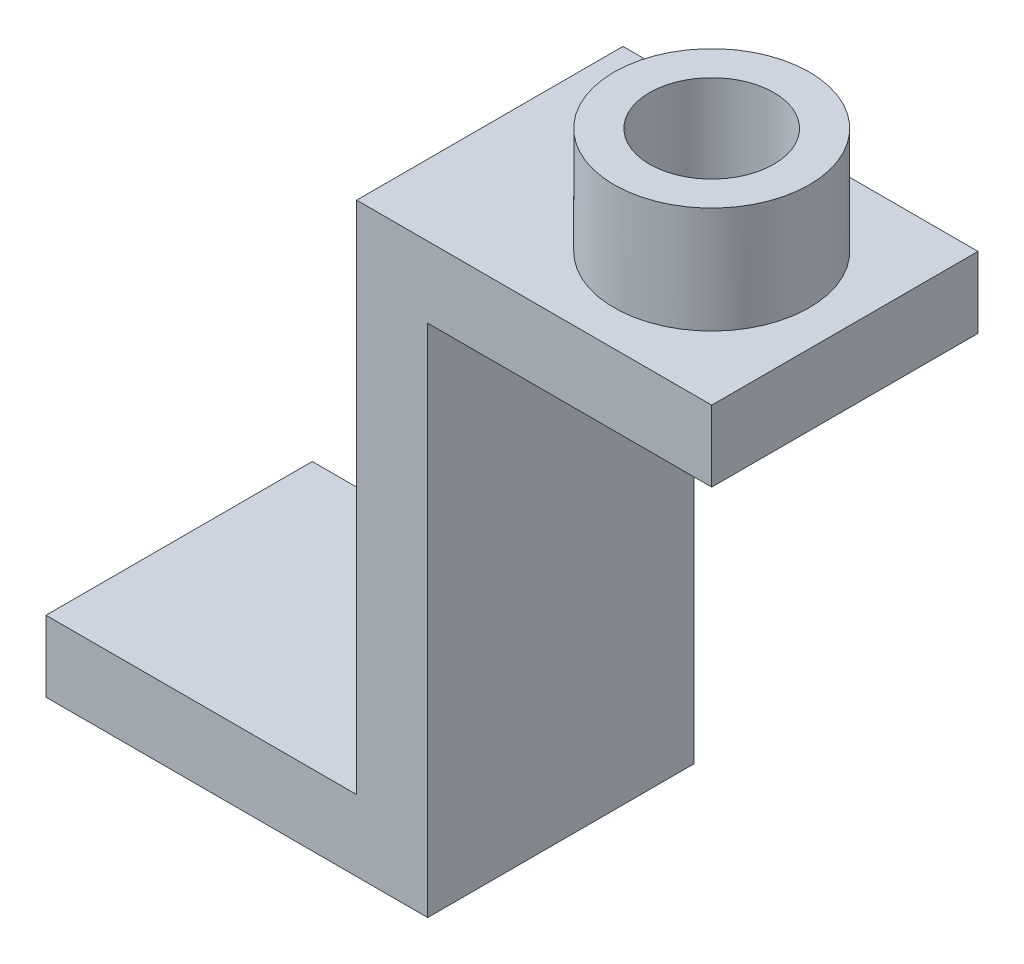
SolidWorks part; units mm, degrees
ref_plane "Front Plane" through (0, 0, 0) normal (0, 0, 1) x (1, 0, 0)
ref_plane "Top Plane" through (0, 0, 0) normal (0, 1, 0) x (1, 0, 0)
ref_plane "Right Plane" through (0, 0, 0) normal (1, 0, 0) x (0, 0, -1)
sketch "Sketch3" plane through (0, 0, 0) normal (0, 0, 1) x (1, 0, 0)
  line L0 (0, 0) -> (43, 0)
  line L1 (43, 0) -> (0, 0)
  line L2 (0, 8) -> (35, 8)
  line L3 (35, 8) -> (0, 8)
  line L4 (35, 8) -> (35, 66)
  line L5 (35, 66) -> (35, 8)
  line L6 (43, 0) -> (43, 58)
  line L7 (43, 58) -> (75, 58)
  line L8 (75, 58) -> (43, 58)
  line L9 (35, 66) -> (75, 66)
  line L10 (75, 66) -> (75, 58)
  line L11 (0, 8) -> (0, 0)
  dimension "D1" = 35
  dimension "D2" = 40
  dimension "D3" = 8
  dimension "D4" = 8
  dimension "D5" = 8
  dimension "D6" = 58
extrude "Boss-Extrude3" add sketch "Sketch3" against normal blind 30 contours L2 L11 L0 L6 L7 L10 L9 L4
sketch "Sketch6" plane through (0, 66, 0) normal (0, 1, 0) x (1, 0, 0)
  line L3 (35, 30) -> (35, 0) construction
  line L4 (35, 0) -> (75, 0) construction
  circle A0 centre (60, 15) radius 7
  circle A1 centre (60, 15) radius 11
  dimension "D1" = 14
  dimension "D2" = 22
  dimension "D3" = 15
  dimension "D4" = 25
extrude "Boss-Extrude4" add sketch "Sketch6" along normal blind 12
sketch "Sketch7" plane through (0, 66, 0) normal (0, 1, 0) x (1, 0, 0)
  circle A0 centre (60, 15) radius 7
  dimension "D1" = 14
extrude "Cut-Extrude1" cut sketch "Sketch7" against normal blind 20
